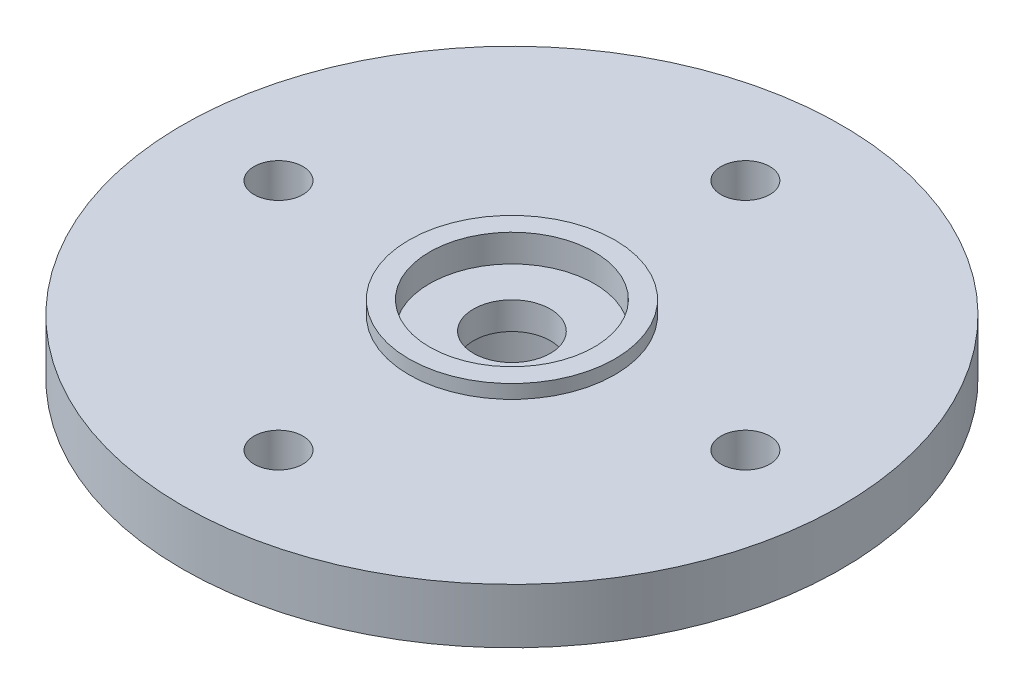
SolidWorks part; units mm, degrees
material "1060 Alloy"
ref_plane "Front Plane" through (0, 0, 0) normal (0, 0, 1) x (1, 0, 0)
ref_plane "Top Plane" through (0, 0, 0) normal (0, 1, 0) x (1, 0, 0)
ref_plane "Right Plane" through (0, 0, 0) normal (1, 0, 0) x (0, 0, -1)
sketch "Sketch1" plane through (0, 0, 0) normal (0, 0, 1) x (1, 0, 0)
  line L0 (0, 0) -> (0, -4.5) construction
  line L1 (0, -55) -> (0, 55) construction
  line L2 (55, 0) -> (-55, 0) construction
  line L3 (-12, 0) -> (-3.75, 0)
  line L4 (-12, 0) -> (-12, -2)
  line L5 (-12, -2) -> (-4.5, -2)
  line L6 (-1.4, 0.5) -> (-1.4, -4.5)
  line L8 (-4.5, -2) -> (-4.5, -4.5)
  line L9 (-4.5, -4.5) -> (-1.4, -4.5)
  line L10 (-3.75, 0.5) -> (-1.4, 0.5)
  line L11 (-3.75, 0.5) -> (-3.75, 0)
  dimension "D1" = 9
  dimension "D2" = 2.5
  dimension "D3" = 4.5
  dimension "D4" = 24
  dimension "D5" = 2.8
  dimension "D6" = 7.5
  dimension "D7" = 5
revolve "Revolve1" add sketch "Sketch1" angle 360 about L0
hole_wizard "#2-56 Tapped Hole1" positions "Sketch3" profile "Sketch2" tap size "#2-56" standard "Ansi Inch" end condition up to next
sketch "Sketch3" plane through (0, 0, 0) normal (0, 1, 0) x (-1, 0, 0)
  circle A0 centre (0, 0) radius 8.5 construction
  point P0 (0, -8.5)
  point P1 (8.5, 0)
  point P3 (-8.5, 0)
  point P5 (0, 8.5)
  dimension "D1" = 17
sketch "Sketch2" plane through (0, 0, -8.5) normal (1, 0, 0) x (0, 0, 1)
  line L0 (0, 0) -> (0, 2)
  line L1 (0, 2) -> (0.889, 2)
  line L2 (0.889, 2) -> (0.889, 0)
  line L5 (0.889, 0) -> (0, 0)
  line L11 (0, -6.35) -> (0, 107.95) construction
  dimension "Thru Tap Drill Dia." = 1.778
  dimension "Thru Tap Drill Depth" = 2
cosmetic thread "Hole Thread1" parameters "D2"=2.1844
cosmetic thread "Hole Thread2" parameters "D2"=2.1844
cosmetic thread "Hole Thread3" parameters "D2"=2.1844
cosmetic thread "Hole Thread4" parameters "D2"=2.1844
sketch "Sketch4" plane through (0, 0.5, 0) normal (0, 1, 0) x (-1, 0, 0)
  circle A0 centre (0, 0) radius 3
  dimension "D1" = 6
extrude "Cut-Extrude1" cut sketch "Sketch4" against normal blind 1
sketch "Sketch5" plane through (0, -4.5, 0) normal (0, -1, 0) x (1, 0, 0)
  circle A0 centre (0, 0) radius 3
  dimension "D1" = 6
extrude "Cut-Extrude2" cut sketch "Sketch5" against normal blind 3
